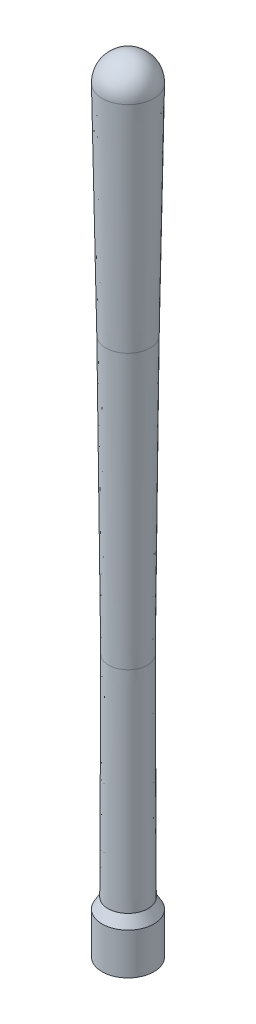
SolidWorks part; units mm, degrees
material "Nylon 101"
ref_plane "Alzado" through (0, 0, 0) normal (0, 0, 1) x (1, 0, 0)
ref_plane "Planta" through (0, 0, 0) normal (0, 1, 0) x (1, 0, 0)
ref_plane "Vista lateral" through (0, 0, 0) normal (1, 0, 0) x (0, 0, -1)
sketch "Sketch1" plane through (0, 0, 0) normal (0, 0, 1) x (1, 0, 0)
  line L0 (0, -8) -> (4.5, -8)
  line L1 (4.5, -8) -> (7.5, -6)
  line L2 (7.5, -6) -> (7.5, 6)
  line L3 (7.5, 6) -> (5.8, 9)
  line L4 (5.8, 9) -> (5.6, 70)
  line L5 (5.6, 70) -> (6.4, 150)
  line L6 (6.4, 150) -> (7.5, 213.4245)
  line L7 (7.5, 213.4245) -> (0, 213.4245)
  line L8 (0, 213.4245) -> (0, -8)
  line L9 (0, -12) -> (0, 217.4245) construction
revolve "Diafisis_y_cabeza" add sketch "Sketch1" angle 360 about L9
sketch "Sketch2" plane through (0, 0, 0) normal (0, 0, 1) x (1, 0, 0)
  line L0 (0, 205.9245) -> (0, 220.9245)
  line L1 (0, 201.9245) -> (0, 224.9245) construction
  arc A0 (0, 220.9245) -> (0, 205.9245) centre (0, 213.4245) cw
revolve "Extremo_proximal" add sketch "Sketch2" angle 360 about L1
